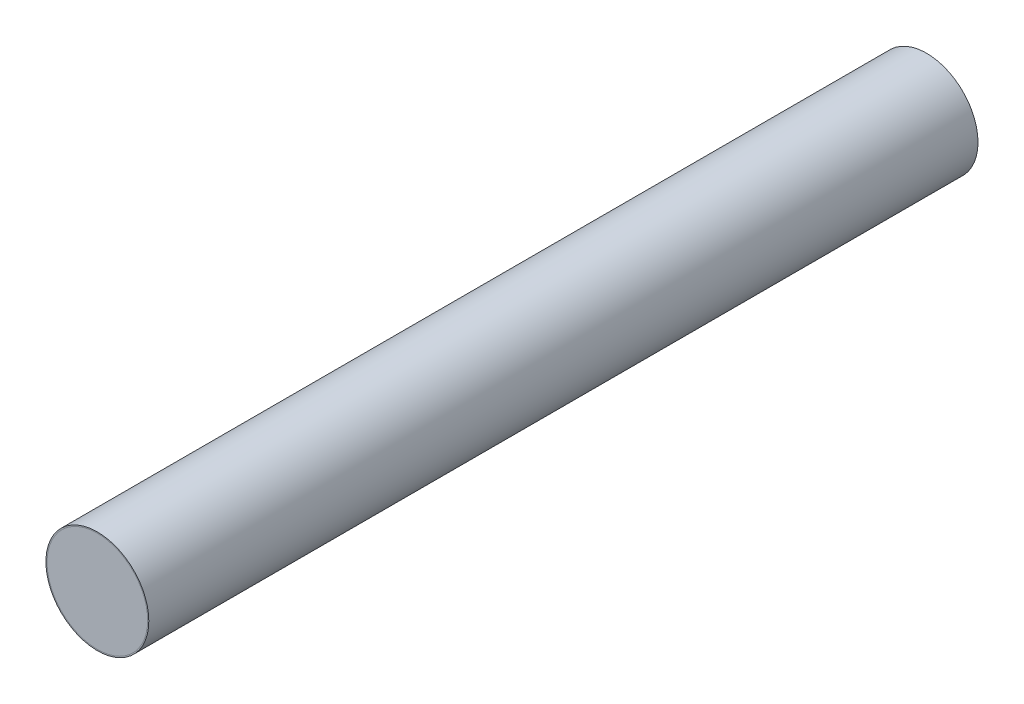
SolidWorks part; units mm, degrees
other "8647WS"
other "03170L"
material "APCP"
ref_plane "Front Plane" through (0, 0, 0) normal (0, 0, 1) x (1, 0, 0)
ref_plane "Top Plane" through (0, 0, 0) normal (0, 1, 0) x (1, 0, 0)
ref_plane "Right Plane" through (0, 0, 0) normal (1, 0, 0) x (0, 0, -1)
sketch "Sketch1" plane through (0, 0, 0) normal (0, 0, 1) x (1, 0, 0)
  circle A0 centre (0, 0) radius 16.5481
  circle A1 centre (0, 0) radius 16.1798
  dimension "D1" = 33.0962
  dimension "D2" = 32.3596
extrude "Boss-Extrude1" add sketch "Sketch1" along normal blind 266.7
sketch "Sketch2" plane through (0, 0, 0) normal (0, 0, 1) x (1, 0, 0)
  circle A0 centre (0, 0) radius 16.1798
  circle A1 centre (0, 0) radius 16.1798 construction
extrude "Boss-Extrude2" add sketch "Sketch2" along normal up to surface (266.7 mm away) separate body up to face at (16.5481, 0, 266.7)
sketch "Sketch3" [suppressed] plane through (0, 0, 72.5424) normal (0, 0, 1) x (1, 0, 0)
  point P0 (0, 0)
hole_wizard "7/16 (0.438) Diameter Hole1" [suppressed] positions "Sketch3" profile "Sketch4" hole size "7/16" standard "ANSI Inch"
sketch "Sketch4" plane through (0, 0, 72.5424) normal (1, 0, 0) x (0, -1, 0)
  line L0 (0, 0) -> (0, 72.5424)
  line L1 (0, 72.5424) -> (5.5626, 72.5424)
  line L2 (5.5626, 72.5424) -> (5.5626, 0)
  line L5 (5.5626, 0) -> (0, 0)
  line L11 (0, -6.35) -> (0, 107.95) construction
  dimension "Thru Hole Dia." = 11.1252
  dimension "Thru Hole Depth" = 72.5424
